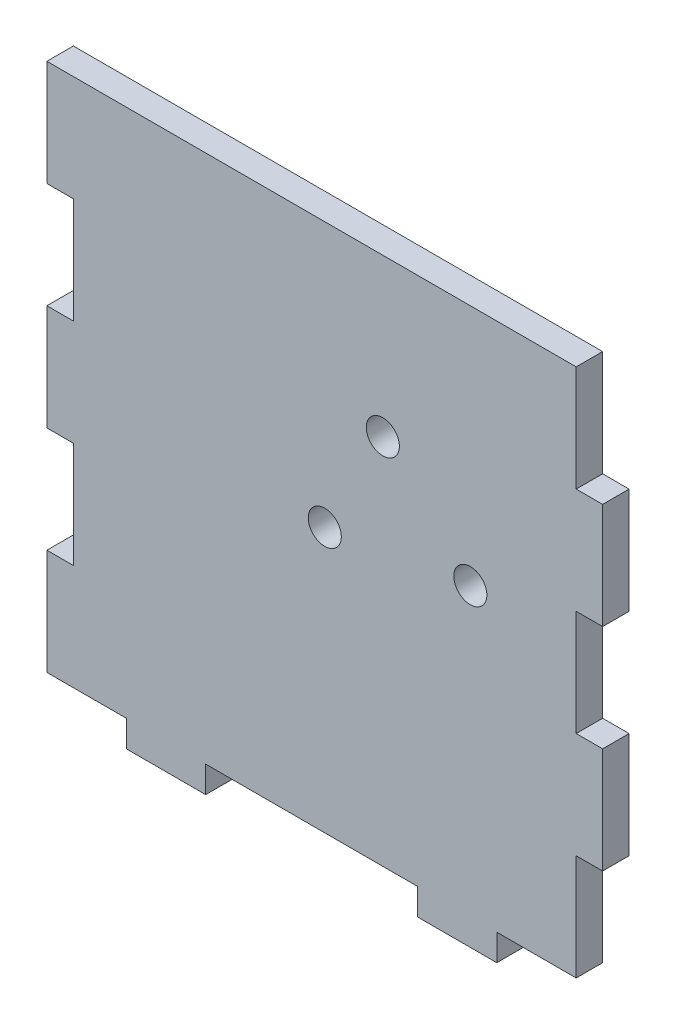
SolidWorks part; units mm, degrees
ref_plane "Front" through (0, 0, 0) normal (0, 0, 1) x (1, 0, 0)
ref_plane "Top" through (0, 0, 0) normal (0, 1, 0) x (1, 0, 0)
ref_plane "Right" through (0, 0, 0) normal (1, 0, 0) x (0, 0, -1)
sketch "Sketch1" plane through (0, 0, 0) normal (0, 0, 1) x (1, 0, 0)
  line L0 (-63.5, 38.1) -> (-63.5, 63.5)
  line L1 (-63.5, -63.5) -> (-44.45, -63.5)
  line L2 (-63.5, -63.5) -> (-63.5, -38.1)
  line L3 (-63.5, 63.5) -> (63.5, 63.5)
  line L4 (63.5, -63.5) -> (63.5, -38.1)
  line L5 (-63.5, -63.5) -> (63.5, 63.5) construction
  line L6 (-63.5, 63.5) -> (63.5, -63.5) construction
  line L7 (-63.5, 38.1) -> (-57.15, 38.1)
  line L8 (-63.5, -12.7) -> (-63.5, 12.7)
  line L9 (-63.5, 12.7) -> (-57.15, 12.7)
  line L10 (-57.15, 38.1) -> (-57.15, 12.7)
  line L11 (-63.5, -12.7) -> (-57.15, -12.7)
  line L12 (63.5, 38.1) -> (63.5, 63.5)
  line L13 (-63.5, -38.1) -> (-57.15, -38.1)
  line L14 (-57.15, -12.7) -> (-57.15, -38.1)
  line L15 (63.5, 38.1) -> (69.85, 38.1)
  line L16 (63.5, -12.7) -> (63.5, 12.7)
  line L17 (63.5, 12.7) -> (69.85, 12.7)
  line L18 (69.85, 38.1) -> (69.85, 12.7)
  line L19 (63.5, -12.7) -> (69.85, -12.7)
  line L20 (-25.4, -63.5) -> (25.4, -63.5)
  line L21 (63.5, -38.1) -> (69.85, -38.1)
  line L22 (69.85, -12.7) -> (69.85, -38.1)
  line L23 (44.45, -63.5) -> (63.5, -63.5)
  line L24 (-44.45, -63.5) -> (-44.45, -69.85)
  line L25 (-44.45, -69.85) -> (-25.4, -69.85)
  line L26 (-25.4, -63.5) -> (-25.4, -69.85)
  line L28 (25.4, -63.5) -> (25.4, -69.85)
  line L29 (25.4, -69.85) -> (44.45, -69.85)
  line L30 (44.45, -63.5) -> (44.45, -69.85)
  point P0 (0, 0)
  dimension "D1" = 127
  dimension "D2" = 127
  dimension "D3" = 6.35
  dimension "D4" = 25.4
  dimension "D5" = 25.4
  dimension "D6" = 25.4
  dimension "D7" = 6.35
  dimension "D8" = 19.05
  dimension "D9" = 19.05
  dimension "D10" = 19.05
extrude "BOXSIDE" add sketch "Sketch1" along normal blind 6.35 contours L3 L12 L15 L18 L17 L16 L19 L22 L21 L4 L23 L30 L29 L28 L20 L26 L25 L24 L1 L2 L13 L14 L11 L8 L9 L10 L7 L0
sketch "Sketch2" plane through (0, 0, 6.35) normal (0, 0, 1) x (1, 0, 0)
  line L0 (69.85, 38.1) -> (69.85, 12.7) construction
  line L1 (44.45, -63.5) -> (63.5, -63.5) construction
  line L2 (38.1, 5.3391) -> (36.83, -19.05) construction
  line L3 (38.1, 5.3391) -> (17.1053, 25.7754) construction
  line L4 (-63.5, -12.7) -> (-63.5, 12.7) construction
  line L6 (17.1053, 25.7754) -> (3.175, 0) construction
  line L7 (63.5, -12.7) -> (63.5, 12.7) construction
  circle A0 centre (36.83, -19.05) radius 3.9687 construction
  circle A1 centre (3.175, 0) radius 3.9688
  circle A2 centre (38.1, 5.3391) radius 3.9687
  circle A4 centre (17.1053, 25.7754) radius 3.9688
  dimension "D1" = 33.02
  dimension "D2" = 7.9375
  dimension "D3" = 44.45
  dimension "D4" = 7.9375
  dimension "D7" = 7.9375
  dimension "D6" = 29.2989
  dimension "D5" = 24.4221
  dimension "D8" = 66.675
  dimension "D9" = 25.4
  dimension "D10" = 29.2989
extrude "Cut-Extrude1" cut sketch "Sketch2" against normal through all
